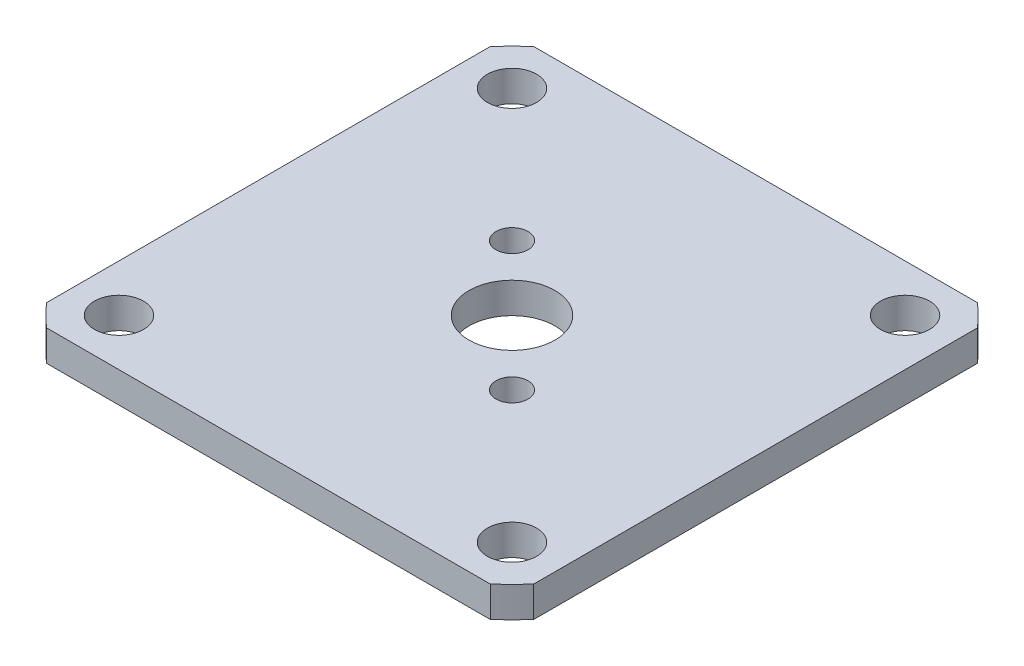
SolidWorks part; units mm, degrees
ref_plane "Front Plane" through (0, 0, 0) normal (0, 0, 1) x (1, 0, 0)
ref_plane "Top Plane" through (0, 0, 0) normal (0, 1, 0) x (1, 0, 0)
ref_plane "Right Plane" through (0, 0, 0) normal (1, 0, 0) x (0, 0, -1)
sketch "Sketch1" plane through (0, 0, 0) normal (0, 1, 0) x (1, 0, 0)
  line L0 (0, 0) -> (-16, 16)
  line L2 (0, 0) -> (-16, 0)
  line L3 (0, 0) -> (0, 16)
  line L4 (0, 16) -> (-16, 16)
  line L5 (-16, 0) -> (-16, 16)
  line L6 (16, -16) -> (-16, -16)
  line L7 (16, -16) -> (16, 16)
  line L8 (16, 16) -> (-16, 16)
  line L9 (-16, -16) -> (-16, 16)
  line L10 (16, -16) -> (-16, 16) construction
  line L11 (16, 16) -> (-16, -16) construction
  circle A0 centre (0, 0) radius 3.5
  circle A1 centre (-16, 16) radius 2
  circle A2 centre (16, 16) radius 2
  circle A3 centre (16, -16) radius 2
  circle A4 centre (-16, -16) radius 2
  circle A5 centre (0, 0) radius 26.83
extrude "Boss-Extrude1" add sketch "Sketch1" along normal blind 2.5 contours A1 L5 L2 A0 L0 | A5 A4 L9 L5 A1 L4 L8 A2 L7 A3 L6 | A4 L6 A3 L7 A2 L8 L3 A0 L2 L9 | A1 L0 A0 L3 L4
sketch "Sketch2" plane through (0, 2.5, 0) normal (0, 1, 0) x (1, 0, 0)
  line L0 (0, 0) -> (-5.2624, -5.2624)
  line L2 (5.2624, 5.2624) -> (-5.2624, 5.2624)
  line L3 (5.2624, 5.2624) -> (5.2624, -5.2624)
  line L4 (5.2624, -5.2624) -> (-5.2624, -5.2624)
  line L5 (-5.2624, 5.2624) -> (-5.2624, -5.2624)
  line L6 (5.2624, 5.2624) -> (-5.2624, -5.2624) construction
  line L7 (5.2624, -5.2624) -> (-5.2624, 5.2624) construction
  circle A0 centre (-5.2624, 5.2624) radius 1.3
  circle A1 centre (5.2624, 5.2624) radius 2
  circle A2 centre (5.2624, -5.2624) radius 1.3
  circle A3 centre (-5.2624, -5.2624) radius 2
sketch "Sketch3" plane through (0, 2.5, 0) normal (0, 1, 0) x (1, 0, 0)
  line L0 (0, 0) -> (16, 16)
  line L1 (16, 16) -> (19.8339, 19.8339)
  line L3 (-19.8339, -19.8339) -> (19.8339, -19.8339)
  line L4 (-19.8339, -19.8339) -> (-19.8339, 19.8339)
  line L5 (-19.8339, 19.8339) -> (19.8339, 19.8339)
  line L6 (19.8339, -19.8339) -> (19.8339, 19.8339)
  line L7 (-19.8339, -19.8339) -> (19.8339, 19.8339) construction
  line L8 (-19.8339, 19.8339) -> (19.8339, -19.8339) construction
  circle M10 centre (0, 0) radius 26.83
extrude "Cut-Extrude2" cut sketch "Sketch3" against normal blind 10 contours L4 M10 | L5 M10 | L6 M10 | L3 M10
extrude "Cut-Extrude3" cut sketch "Sketch2" against normal blind 10 contours A0 | A2
